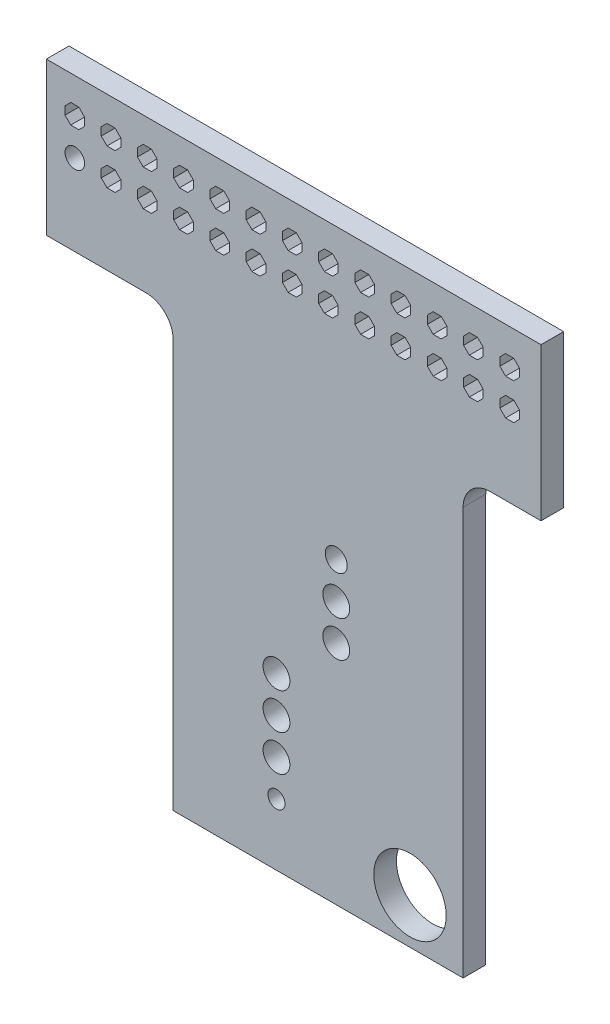
SolidWorks part; units mm, degrees
ref_plane "Front Plane" through (0, 0, 0) normal (0, 0, 1) x (1, 0, 0)
ref_plane "Top Plane" through (0, 0, 0) normal (0, 1, 0) x (1, 0, 0)
ref_plane "Right Plane" through (0, 0, 0) normal (1, 0, 0) x (0, 0, -1)
sketch "Model" plane through (0, 0, 0) normal (0, 0, 1) x (1, 0, 0)
  line L0 (16.129, 5.2578) -> (16.129, 3.3782) construction
  line L1 (20.32, 21.8948) -> (20.32, 20.0152) construction
  line L8 (19.3802, 21.8948) -> (19.3802, 20.0152) construction
  line L9 (19.3802, 20.0152) -> (21.2598, 20.0152) construction
  line L10 (21.2598, 20.0152) -> (21.2598, 21.8948) construction
  line L11 (21.2598, 21.8948) -> (19.3802, 21.8948) construction
  line L12 (19.3802, 21.8948) -> (19.3802, 20.0152) construction
  line L13 (19.3802, 20.0152) -> (21.2598, 20.0152) construction
  line L14 (21.2598, 20.0152) -> (21.2598, 21.8948) construction
  line L15 (21.2598, 21.8948) -> (19.3802, 21.8948) construction
  line L16 (17.0688, 3.3782) -> (17.0688, 5.2578) construction
  line L17 (17.0688, 5.2578) -> (15.1892, 5.2578) construction
  line L18 (15.1892, 5.2578) -> (15.1892, 3.3782) construction
  line L19 (15.1892, 3.3782) -> (17.0688, 3.3782) construction
  line L20 (17.0688, 3.3782) -> (17.0688, 5.2578) construction
  line L21 (17.0688, 5.2578) -> (15.1892, 5.2578) construction
  line L22 (15.1892, 5.2578) -> (15.1892, 3.3782) construction
  line L23 (15.1892, 3.3782) -> (17.0688, 3.3782) construction
  line L24 (8.89, 0) -> (29.21, 0)
  line L25 (34.671, 41.1734) -> (0, 41.1734)
  line L26 (0, 41.1734) -> (0, 30.48)
  line L27 (0, 30.48) -> (6.985, 30.48)
  line L28 (8.89, 28.575) -> (8.89, 0)
  line L29 (29.21, 28.575) -> (29.21, 0)
  line L30 (34.671, 30.48) -> (34.671, 41.1734)
  line L31 (34.671, 30.48) -> (31.115, 30.48)
  circle A0 centre (16.129, 4.318) radius 0.5995
  circle A1 centre (20.32, 20.955) radius 0.7709
  arc A2 (8.89, 28.575) -> (6.985, 30.48) centre (6.985, 28.575) ccw
  arc A3 (31.115, 30.48) -> (29.21, 28.575) centre (31.115, 28.575) ccw
  circle B0 centre (1.9939, 36.1696) radius 0.6858
  circle B1 centre (1.9939, 36.1696) radius 0.6858
  line B2 (1.3081, 38.4255) -> (1.3081, 38.9937)
  line B3 (1.3081, 38.9937) -> (1.7098, 39.3954)
  line B4 (1.7098, 39.3954) -> (2.278, 39.3954)
  line B5 (2.278, 39.3954) -> (2.6797, 38.9937)
  line B6 (2.6797, 38.9937) -> (2.6797, 38.4255)
  line B7 (2.6797, 38.4255) -> (2.278, 38.0238)
  line B8 (2.278, 38.0238) -> (1.7098, 38.0238)
  line B9 (1.7098, 38.0238) -> (1.3081, 38.4255)
  line B10 (1.3081, 38.4255) -> (1.3081, 38.9937)
  line B11 (1.3081, 38.9937) -> (1.7098, 39.3954)
  line B12 (1.7098, 39.3954) -> (2.278, 39.3954)
  line B13 (2.278, 39.3954) -> (2.6797, 38.9937)
  line B14 (2.6797, 38.9937) -> (2.6797, 38.4255)
  line B15 (2.6797, 38.4255) -> (2.278, 38.0238)
  line B16 (2.278, 38.0238) -> (1.7098, 38.0238)
  line B17 (1.7098, 38.0238) -> (1.3081, 38.4255)
  line B18 (3.8481, 35.8855) -> (3.8481, 36.4537)
  line B19 (3.8481, 36.4537) -> (4.2498, 36.8554)
  line B20 (4.2498, 36.8554) -> (4.818, 36.8554)
  line B21 (4.818, 36.8554) -> (5.2197, 36.4537)
  line B22 (5.2197, 36.4537) -> (5.2197, 35.8855)
  line B23 (5.2197, 35.8855) -> (4.818, 35.4838)
  line B24 (4.818, 35.4838) -> (4.2498, 35.4838)
  line B25 (4.2498, 35.4838) -> (3.8481, 35.8855)
  line B26 (3.8481, 35.8855) -> (3.8481, 36.4537)
  line B27 (3.8481, 36.4537) -> (4.2498, 36.8554)
  line B28 (4.2498, 36.8554) -> (4.818, 36.8554)
  line B29 (4.818, 36.8554) -> (5.2197, 36.4537)
  line B30 (5.2197, 36.4537) -> (5.2197, 35.8855)
  line B31 (5.2197, 35.8855) -> (4.818, 35.4838)
  line B32 (4.818, 35.4838) -> (4.2498, 35.4838)
  line B33 (4.2498, 35.4838) -> (3.8481, 35.8855)
  line B34 (3.8481, 38.4255) -> (3.8481, 38.9937)
  line B35 (3.8481, 38.9937) -> (4.2498, 39.3954)
  line B36 (4.2498, 39.3954) -> (4.818, 39.3954)
  line B37 (4.818, 39.3954) -> (5.2197, 38.9937)
  line B38 (5.2197, 38.9937) -> (5.2197, 38.4255)
  line B39 (5.2197, 38.4255) -> (4.818, 38.0238)
  line B40 (4.818, 38.0238) -> (4.2498, 38.0238)
  line B41 (4.2498, 38.0238) -> (3.8481, 38.4255)
  line B42 (3.8481, 38.4255) -> (3.8481, 38.9937)
  line B43 (3.8481, 38.9937) -> (4.2498, 39.3954)
  line B44 (4.2498, 39.3954) -> (4.818, 39.3954)
  line B45 (4.818, 39.3954) -> (5.2197, 38.9937)
  line B46 (5.2197, 38.9937) -> (5.2197, 38.4255)
  line B47 (5.2197, 38.4255) -> (4.818, 38.0238)
  line B48 (4.818, 38.0238) -> (4.2498, 38.0238)
  line B49 (4.2498, 38.0238) -> (3.8481, 38.4255)
  line B50 (6.3881, 35.8855) -> (6.3881, 36.4537)
  line B51 (6.3881, 36.4537) -> (6.7898, 36.8554)
  line B52 (6.7898, 36.8554) -> (7.358, 36.8554)
  line B53 (7.358, 36.8554) -> (7.7597, 36.4537)
  line B54 (7.7597, 36.4537) -> (7.7597, 35.8855)
  line B55 (7.7597, 35.8855) -> (7.358, 35.4838)
  line B56 (7.358, 35.4838) -> (6.7898, 35.4838)
  line B57 (6.7898, 35.4838) -> (6.3881, 35.8855)
  line B58 (6.3881, 35.8855) -> (6.3881, 36.4537)
  line B59 (6.3881, 36.4537) -> (6.7898, 36.8554)
  line B60 (6.7898, 36.8554) -> (7.358, 36.8554)
  line B61 (7.358, 36.8554) -> (7.7597, 36.4537)
  line B62 (7.7597, 36.4537) -> (7.7597, 35.8855)
  line B63 (7.7597, 35.8855) -> (7.358, 35.4838)
  line B64 (7.358, 35.4838) -> (6.7898, 35.4838)
  line B65 (6.7898, 35.4838) -> (6.3881, 35.8855)
  line B66 (6.3881, 38.4255) -> (6.3881, 38.9937)
  line B67 (6.3881, 38.9937) -> (6.7898, 39.3954)
  line B68 (6.7898, 39.3954) -> (7.358, 39.3954)
  line B69 (7.358, 39.3954) -> (7.7597, 38.9937)
  line B70 (7.7597, 38.9937) -> (7.7597, 38.4255)
  line B71 (7.7597, 38.4255) -> (7.358, 38.0238)
  line B72 (7.358, 38.0238) -> (6.7898, 38.0238)
  line B73 (6.7898, 38.0238) -> (6.3881, 38.4255)
  line B74 (6.3881, 38.4255) -> (6.3881, 38.9937)
  line B75 (6.3881, 38.9937) -> (6.7898, 39.3954)
  line B76 (6.7898, 39.3954) -> (7.358, 39.3954)
  line B77 (7.358, 39.3954) -> (7.7597, 38.9937)
  line B78 (7.7597, 38.9937) -> (7.7597, 38.4255)
  line B79 (7.7597, 38.4255) -> (7.358, 38.0238)
  line B80 (7.358, 38.0238) -> (6.7898, 38.0238)
  line B81 (6.7898, 38.0238) -> (6.3881, 38.4255)
  line B82 (8.9281, 35.8855) -> (8.9281, 36.4537)
  line B83 (8.9281, 36.4537) -> (9.3298, 36.8554)
  line B84 (9.3298, 36.8554) -> (9.898, 36.8554)
  line B85 (9.898, 36.8554) -> (10.2997, 36.4537)
  line B86 (10.2997, 36.4537) -> (10.2997, 35.8855)
  line B87 (10.2997, 35.8855) -> (9.898, 35.4838)
  line B88 (9.898, 35.4838) -> (9.3298, 35.4838)
  line B89 (9.3298, 35.4838) -> (8.9281, 35.8855)
  line B90 (8.9281, 35.8855) -> (8.9281, 36.4537)
  line B91 (8.9281, 36.4537) -> (9.3298, 36.8554)
  line B92 (9.3298, 36.8554) -> (9.898, 36.8554)
  line B93 (9.898, 36.8554) -> (10.2997, 36.4537)
  line B94 (10.2997, 36.4537) -> (10.2997, 35.8855)
  line B95 (10.2997, 35.8855) -> (9.898, 35.4838)
  line B96 (9.898, 35.4838) -> (9.3298, 35.4838)
  line B97 (9.3298, 35.4838) -> (8.9281, 35.8855)
  line B98 (8.9281, 38.4255) -> (8.9281, 38.9937)
  line B99 (8.9281, 38.9937) -> (9.3298, 39.3954)
  line B100 (9.3298, 39.3954) -> (9.898, 39.3954)
  line B101 (9.898, 39.3954) -> (10.2997, 38.9937)
  line B102 (10.2997, 38.9937) -> (10.2997, 38.4255)
  line B103 (10.2997, 38.4255) -> (9.898, 38.0238)
  line B104 (9.898, 38.0238) -> (9.3298, 38.0238)
  line B105 (9.3298, 38.0238) -> (8.9281, 38.4255)
  line B106 (8.9281, 38.4255) -> (8.9281, 38.9937)
  line B107 (8.9281, 38.9937) -> (9.3298, 39.3954)
  line B108 (9.3298, 39.3954) -> (9.898, 39.3954)
  line B109 (9.898, 39.3954) -> (10.2997, 38.9937)
  line B110 (10.2997, 38.9937) -> (10.2997, 38.4255)
  line B111 (10.2997, 38.4255) -> (9.898, 38.0238)
  line B112 (9.898, 38.0238) -> (9.3298, 38.0238)
  line B113 (9.3298, 38.0238) -> (8.9281, 38.4255)
  line B114 (11.4681, 35.8855) -> (11.4681, 36.4537)
  line B115 (11.4681, 36.4537) -> (11.8698, 36.8554)
  line B116 (11.8698, 36.8554) -> (12.438, 36.8554)
  line B117 (12.438, 36.8554) -> (12.8397, 36.4537)
  line B118 (12.8397, 36.4537) -> (12.8397, 35.8855)
  line B119 (12.8397, 35.8855) -> (12.438, 35.4838)
  line B120 (12.438, 35.4838) -> (11.8698, 35.4838)
  line B121 (11.8698, 35.4838) -> (11.4681, 35.8855)
  line B122 (11.4681, 35.8855) -> (11.4681, 36.4537)
  line B123 (11.4681, 36.4537) -> (11.8698, 36.8554)
  line B124 (11.8698, 36.8554) -> (12.438, 36.8554)
  line B125 (12.438, 36.8554) -> (12.8397, 36.4537)
  line B126 (12.8397, 36.4537) -> (12.8397, 35.8855)
  line B127 (12.8397, 35.8855) -> (12.438, 35.4838)
  line B128 (12.438, 35.4838) -> (11.8698, 35.4838)
  line B129 (11.8698, 35.4838) -> (11.4681, 35.8855)
  line B130 (11.4681, 38.4255) -> (11.4681, 38.9937)
  line B131 (11.4681, 38.9937) -> (11.8698, 39.3954)
  line B132 (11.8698, 39.3954) -> (12.438, 39.3954)
  line B133 (12.438, 39.3954) -> (12.8397, 38.9937)
  line B134 (12.8397, 38.9937) -> (12.8397, 38.4255)
  line B135 (12.8397, 38.4255) -> (12.438, 38.0238)
  line B136 (12.438, 38.0238) -> (11.8698, 38.0238)
  line B137 (11.8698, 38.0238) -> (11.4681, 38.4255)
  line B138 (11.4681, 38.4255) -> (11.4681, 38.9937)
  line B139 (11.4681, 38.9937) -> (11.8698, 39.3954)
  line B140 (11.8698, 39.3954) -> (12.438, 39.3954)
  line B141 (12.438, 39.3954) -> (12.8397, 38.9937)
  line B142 (12.8397, 38.9937) -> (12.8397, 38.4255)
  line B143 (12.8397, 38.4255) -> (12.438, 38.0238)
  line B144 (12.438, 38.0238) -> (11.8698, 38.0238)
  line B145 (11.8698, 38.0238) -> (11.4681, 38.4255)
  line B146 (14.0081, 35.8855) -> (14.0081, 36.4537)
  line B147 (14.0081, 36.4537) -> (14.4098, 36.8554)
  line B148 (14.4098, 36.8554) -> (14.978, 36.8554)
  line B149 (14.978, 36.8554) -> (15.3797, 36.4537)
  line B150 (15.3797, 36.4537) -> (15.3797, 35.8855)
  line B151 (15.3797, 35.8855) -> (14.978, 35.4838)
  line B152 (14.978, 35.4838) -> (14.4098, 35.4838)
  line B153 (14.4098, 35.4838) -> (14.0081, 35.8855)
  line B154 (14.0081, 35.8855) -> (14.0081, 36.4537)
  line B155 (14.0081, 36.4537) -> (14.4098, 36.8554)
  line B156 (14.4098, 36.8554) -> (14.978, 36.8554)
  line B157 (14.978, 36.8554) -> (15.3797, 36.4537)
  line B158 (15.3797, 36.4537) -> (15.3797, 35.8855)
  line B159 (15.3797, 35.8855) -> (14.978, 35.4838)
  line B160 (14.978, 35.4838) -> (14.4098, 35.4838)
  line B161 (14.4098, 35.4838) -> (14.0081, 35.8855)
  line B162 (14.0081, 38.4255) -> (14.0081, 38.9937)
  line B163 (14.0081, 38.9937) -> (14.4098, 39.3954)
  line B164 (14.4098, 39.3954) -> (14.978, 39.3954)
  line B165 (14.978, 39.3954) -> (15.3797, 38.9937)
  line B166 (15.3797, 38.9937) -> (15.3797, 38.4255)
  line B167 (15.3797, 38.4255) -> (14.978, 38.0238)
  line B168 (14.978, 38.0238) -> (14.4098, 38.0238)
  line B169 (14.4098, 38.0238) -> (14.0081, 38.4255)
  line B170 (14.0081, 38.4255) -> (14.0081, 38.9937)
  line B171 (14.0081, 38.9937) -> (14.4098, 39.3954)
  line B172 (14.4098, 39.3954) -> (14.978, 39.3954)
  line B173 (14.978, 39.3954) -> (15.3797, 38.9937)
  line B174 (15.3797, 38.9937) -> (15.3797, 38.4255)
  line B175 (15.3797, 38.4255) -> (14.978, 38.0238)
  line B176 (14.978, 38.0238) -> (14.4098, 38.0238)
  line B177 (14.4098, 38.0238) -> (14.0081, 38.4255)
  line B178 (16.5481, 35.8855) -> (16.5481, 36.4537)
  line B179 (16.5481, 36.4537) -> (16.9498, 36.8554)
  line B180 (16.9498, 36.8554) -> (17.518, 36.8554)
  line B181 (17.518, 36.8554) -> (17.9197, 36.4537)
  line B182 (17.9197, 36.4537) -> (17.9197, 35.8855)
  line B183 (17.9197, 35.8855) -> (17.518, 35.4838)
  line B184 (17.518, 35.4838) -> (16.9498, 35.4838)
  line B185 (16.9498, 35.4838) -> (16.5481, 35.8855)
  line B186 (16.5481, 35.8855) -> (16.5481, 36.4537)
  line B187 (16.5481, 36.4537) -> (16.9498, 36.8554)
  line B188 (16.9498, 36.8554) -> (17.518, 36.8554)
  line B189 (17.518, 36.8554) -> (17.9197, 36.4537)
  line B190 (17.9197, 36.4537) -> (17.9197, 35.8855)
  line B191 (17.9197, 35.8855) -> (17.518, 35.4838)
  line B192 (17.518, 35.4838) -> (16.9498, 35.4838)
  line B193 (16.9498, 35.4838) -> (16.5481, 35.8855)
  line B194 (16.5481, 38.4255) -> (16.5481, 38.9937)
  line B195 (16.5481, 38.9937) -> (16.9498, 39.3954)
  line B196 (16.9498, 39.3954) -> (17.518, 39.3954)
  line B197 (17.518, 39.3954) -> (17.9197, 38.9937)
  line B198 (17.9197, 38.9937) -> (17.9197, 38.4255)
  line B199 (17.9197, 38.4255) -> (17.518, 38.0238)
  line B200 (17.518, 38.0238) -> (16.9498, 38.0238)
  line B201 (16.9498, 38.0238) -> (16.5481, 38.4255)
  line B202 (16.5481, 38.4255) -> (16.5481, 38.9937)
  line B203 (16.5481, 38.9937) -> (16.9498, 39.3954)
  line B204 (16.9498, 39.3954) -> (17.518, 39.3954)
  line B205 (17.518, 39.3954) -> (17.9197, 38.9937)
  line B206 (17.9197, 38.9937) -> (17.9197, 38.4255)
  line B207 (17.9197, 38.4255) -> (17.518, 38.0238)
  line B208 (17.518, 38.0238) -> (16.9498, 38.0238)
  line B209 (16.9498, 38.0238) -> (16.5481, 38.4255)
  line B210 (19.0881, 35.8855) -> (19.0881, 36.4537)
  line B211 (19.0881, 36.4537) -> (19.4898, 36.8554)
  line B212 (19.4898, 36.8554) -> (20.058, 36.8554)
  line B213 (20.058, 36.8554) -> (20.4597, 36.4537)
  line B214 (20.4597, 36.4537) -> (20.4597, 35.8855)
  line B215 (20.4597, 35.8855) -> (20.058, 35.4838)
  line B216 (20.058, 35.4838) -> (19.4898, 35.4838)
  line B217 (19.4898, 35.4838) -> (19.0881, 35.8855)
  line B218 (19.0881, 35.8855) -> (19.0881, 36.4537)
  line B219 (19.0881, 36.4537) -> (19.4898, 36.8554)
  line B220 (19.4898, 36.8554) -> (20.058, 36.8554)
  line B221 (20.058, 36.8554) -> (20.4597, 36.4537)
  line B222 (20.4597, 36.4537) -> (20.4597, 35.8855)
  line B223 (20.4597, 35.8855) -> (20.058, 35.4838)
  line B224 (20.058, 35.4838) -> (19.4898, 35.4838)
  line B225 (19.4898, 35.4838) -> (19.0881, 35.8855)
  line B226 (19.0881, 38.4255) -> (19.0881, 38.9937)
  line B227 (19.0881, 38.9937) -> (19.4898, 39.3954)
  line B228 (19.4898, 39.3954) -> (20.058, 39.3954)
  line B229 (20.058, 39.3954) -> (20.4597, 38.9937)
  line B230 (20.4597, 38.9937) -> (20.4597, 38.4255)
  line B231 (20.4597, 38.4255) -> (20.058, 38.0238)
  line B232 (20.058, 38.0238) -> (19.4898, 38.0238)
  line B233 (19.4898, 38.0238) -> (19.0881, 38.4255)
  line B234 (19.0881, 38.4255) -> (19.0881, 38.9937)
  line B235 (19.0881, 38.9937) -> (19.4898, 39.3954)
  line B236 (19.4898, 39.3954) -> (20.058, 39.3954)
  line B237 (20.058, 39.3954) -> (20.4597, 38.9937)
  line B238 (20.4597, 38.9937) -> (20.4597, 38.4255)
  line B239 (20.4597, 38.4255) -> (20.058, 38.0238)
  line B240 (20.058, 38.0238) -> (19.4898, 38.0238)
  line B241 (19.4898, 38.0238) -> (19.0881, 38.4255)
  line B242 (21.6281, 35.8855) -> (21.6281, 36.4537)
  line B243 (21.6281, 36.4537) -> (22.0298, 36.8554)
  line B244 (22.0298, 36.8554) -> (22.598, 36.8554)
  line B245 (22.598, 36.8554) -> (22.9997, 36.4537)
  line B246 (22.9997, 36.4537) -> (22.9997, 35.8855)
  line B247 (22.9997, 35.8855) -> (22.598, 35.4838)
  line B248 (22.598, 35.4838) -> (22.0298, 35.4838)
  line B249 (22.0298, 35.4838) -> (21.6281, 35.8855)
  line B250 (21.6281, 35.8855) -> (21.6281, 36.4537)
  line B251 (21.6281, 36.4537) -> (22.0298, 36.8554)
  line B252 (22.0298, 36.8554) -> (22.598, 36.8554)
  line B253 (22.598, 36.8554) -> (22.9997, 36.4537)
  line B254 (22.9997, 36.4537) -> (22.9997, 35.8855)
  line B255 (22.9997, 35.8855) -> (22.598, 35.4838)
  line B256 (22.598, 35.4838) -> (22.0298, 35.4838)
  line B257 (22.0298, 35.4838) -> (21.6281, 35.8855)
  line B258 (21.6281, 38.4255) -> (21.6281, 38.9937)
  line B259 (21.6281, 38.9937) -> (22.0298, 39.3954)
  line B260 (22.0298, 39.3954) -> (22.598, 39.3954)
  line B261 (22.598, 39.3954) -> (22.9997, 38.9937)
  line B262 (22.9997, 38.9937) -> (22.9997, 38.4255)
  line B263 (22.9997, 38.4255) -> (22.598, 38.0238)
  line B264 (22.598, 38.0238) -> (22.0298, 38.0238)
  line B265 (22.0298, 38.0238) -> (21.6281, 38.4255)
  line B266 (21.6281, 38.4255) -> (21.6281, 38.9937)
  line B267 (21.6281, 38.9937) -> (22.0298, 39.3954)
  line B268 (22.0298, 39.3954) -> (22.598, 39.3954)
  line B269 (22.598, 39.3954) -> (22.9997, 38.9937)
  line B270 (22.9997, 38.9937) -> (22.9997, 38.4255)
  line B271 (22.9997, 38.4255) -> (22.598, 38.0238)
  line B272 (22.598, 38.0238) -> (22.0298, 38.0238)
  line B273 (22.0298, 38.0238) -> (21.6281, 38.4255)
  line B274 (24.1681, 35.8855) -> (24.1681, 36.4537)
  line B275 (24.1681, 36.4537) -> (24.5698, 36.8554)
  line B276 (24.5698, 36.8554) -> (25.138, 36.8554)
  line B277 (25.138, 36.8554) -> (25.5397, 36.4537)
  line B278 (25.5397, 36.4537) -> (25.5397, 35.8855)
  line B279 (25.5397, 35.8855) -> (25.138, 35.4838)
  line B280 (25.138, 35.4838) -> (24.5698, 35.4838)
  line B281 (24.5698, 35.4838) -> (24.1681, 35.8855)
  line B282 (24.1681, 35.8855) -> (24.1681, 36.4537)
  line B283 (24.1681, 36.4537) -> (24.5698, 36.8554)
  line B284 (24.5698, 36.8554) -> (25.138, 36.8554)
  line B285 (25.138, 36.8554) -> (25.5397, 36.4537)
  line B286 (25.5397, 36.4537) -> (25.5397, 35.8855)
  line B287 (25.5397, 35.8855) -> (25.138, 35.4838)
  line B288 (25.138, 35.4838) -> (24.5698, 35.4838)
  line B289 (24.5698, 35.4838) -> (24.1681, 35.8855)
  line B290 (24.1681, 38.4255) -> (24.1681, 38.9937)
  line B291 (24.1681, 38.9937) -> (24.5698, 39.3954)
  line B292 (24.5698, 39.3954) -> (25.138, 39.3954)
  line B293 (25.138, 39.3954) -> (25.5397, 38.9937)
  line B294 (25.5397, 38.9937) -> (25.5397, 38.4255)
  line B295 (25.5397, 38.4255) -> (25.138, 38.0238)
  line B296 (25.138, 38.0238) -> (24.5698, 38.0238)
  line B297 (24.5698, 38.0238) -> (24.1681, 38.4255)
  line B298 (24.1681, 38.4255) -> (24.1681, 38.9937)
  line B299 (24.1681, 38.9937) -> (24.5698, 39.3954)
  line B300 (24.5698, 39.3954) -> (25.138, 39.3954)
  line B301 (25.138, 39.3954) -> (25.5397, 38.9937)
  line B302 (25.5397, 38.9937) -> (25.5397, 38.4255)
  line B303 (25.5397, 38.4255) -> (25.138, 38.0238)
  line B304 (25.138, 38.0238) -> (24.5698, 38.0238)
  line B305 (24.5698, 38.0238) -> (24.1681, 38.4255)
  line B306 (26.7081, 35.8855) -> (26.7081, 36.4537)
  line B307 (26.7081, 36.4537) -> (27.1098, 36.8554)
  line B308 (27.1098, 36.8554) -> (27.678, 36.8554)
  line B309 (27.678, 36.8554) -> (28.0797, 36.4537)
  line B310 (28.0797, 36.4537) -> (28.0797, 35.8855)
  line B311 (28.0797, 35.8855) -> (27.678, 35.4838)
  line B312 (27.678, 35.4838) -> (27.1098, 35.4838)
  line B313 (27.1098, 35.4838) -> (26.7081, 35.8855)
  line B314 (26.7081, 35.8855) -> (26.7081, 36.4537)
  line B315 (26.7081, 36.4537) -> (27.1098, 36.8554)
  line B316 (27.1098, 36.8554) -> (27.678, 36.8554)
  line B317 (27.678, 36.8554) -> (28.0797, 36.4537)
  line B318 (28.0797, 36.4537) -> (28.0797, 35.8855)
  line B319 (28.0797, 35.8855) -> (27.678, 35.4838)
  line B320 (27.678, 35.4838) -> (27.1098, 35.4838)
  line B321 (27.1098, 35.4838) -> (26.7081, 35.8855)
  line B322 (26.7081, 38.4255) -> (26.7081, 38.9937)
  line B323 (26.7081, 38.9937) -> (27.1098, 39.3954)
  line B324 (27.1098, 39.3954) -> (27.678, 39.3954)
  line B325 (27.678, 39.3954) -> (28.0797, 38.9937)
  line B326 (28.0797, 38.9937) -> (28.0797, 38.4255)
  line B327 (28.0797, 38.4255) -> (27.678, 38.0238)
  line B328 (27.678, 38.0238) -> (27.1098, 38.0238)
  line B329 (27.1098, 38.0238) -> (26.7081, 38.4255)
  line B330 (26.7081, 38.4255) -> (26.7081, 38.9937)
  line B331 (26.7081, 38.9937) -> (27.1098, 39.3954)
  line B332 (27.1098, 39.3954) -> (27.678, 39.3954)
  line B333 (27.678, 39.3954) -> (28.0797, 38.9937)
  line B334 (28.0797, 38.9937) -> (28.0797, 38.4255)
  line B335 (28.0797, 38.4255) -> (27.678, 38.0238)
  line B336 (27.678, 38.0238) -> (27.1098, 38.0238)
  line B337 (27.1098, 38.0238) -> (26.7081, 38.4255)
  line B338 (29.2481, 35.8855) -> (29.2481, 36.4537)
  line B339 (29.2481, 36.4537) -> (29.6498, 36.8554)
  line B340 (29.6498, 36.8554) -> (30.218, 36.8554)
  line B341 (30.218, 36.8554) -> (30.6197, 36.4537)
  line B342 (30.6197, 36.4537) -> (30.6197, 35.8855)
  line B343 (30.6197, 35.8855) -> (30.218, 35.4838)
  line B344 (30.218, 35.4838) -> (29.6498, 35.4838)
  line B345 (29.6498, 35.4838) -> (29.2481, 35.8855)
  line B346 (29.2481, 35.8855) -> (29.2481, 36.4537)
  line B347 (29.2481, 36.4537) -> (29.6498, 36.8554)
  line B348 (29.6498, 36.8554) -> (30.218, 36.8554)
  line B349 (30.218, 36.8554) -> (30.6197, 36.4537)
  line B350 (30.6197, 36.4537) -> (30.6197, 35.8855)
  line B351 (30.6197, 35.8855) -> (30.218, 35.4838)
  line B352 (30.218, 35.4838) -> (29.6498, 35.4838)
  line B353 (29.6498, 35.4838) -> (29.2481, 35.8855)
  line B354 (29.2481, 38.4255) -> (29.2481, 38.9937)
  line B355 (29.2481, 38.9937) -> (29.6498, 39.3954)
  line B356 (29.6498, 39.3954) -> (30.218, 39.3954)
  line B357 (30.218, 39.3954) -> (30.6197, 38.9937)
  line B358 (30.6197, 38.9937) -> (30.6197, 38.4255)
  line B359 (30.6197, 38.4255) -> (30.218, 38.0238)
  line B360 (30.218, 38.0238) -> (29.6498, 38.0238)
  line B361 (29.6498, 38.0238) -> (29.2481, 38.4255)
  line B362 (29.2481, 38.4255) -> (29.2481, 38.9937)
  line B363 (29.2481, 38.9937) -> (29.6498, 39.3954)
  line B364 (29.6498, 39.3954) -> (30.218, 39.3954)
  line B365 (30.218, 39.3954) -> (30.6197, 38.9937)
  line B366 (30.6197, 38.9937) -> (30.6197, 38.4255)
  line B367 (30.6197, 38.4255) -> (30.218, 38.0238)
  line B368 (30.218, 38.0238) -> (29.6498, 38.0238)
  line B369 (29.6498, 38.0238) -> (29.2481, 38.4255)
  line B370 (31.7881, 35.8855) -> (31.7881, 36.4537)
  line B371 (31.7881, 36.4537) -> (32.1898, 36.8554)
  line B372 (32.1898, 36.8554) -> (32.758, 36.8554)
  line B373 (32.758, 36.8554) -> (33.1597, 36.4537)
  line B374 (33.1597, 36.4537) -> (33.1597, 35.8855)
  line B375 (33.1597, 35.8855) -> (32.758, 35.4838)
  line B376 (32.758, 35.4838) -> (32.1898, 35.4838)
  line B377 (32.1898, 35.4838) -> (31.7881, 35.8855)
  line B378 (31.7881, 35.8855) -> (31.7881, 36.4537)
  line B379 (31.7881, 36.4537) -> (32.1898, 36.8554)
  line B380 (32.1898, 36.8554) -> (32.758, 36.8554)
  line B381 (32.758, 36.8554) -> (33.1597, 36.4537)
  line B382 (33.1597, 36.4537) -> (33.1597, 35.8855)
  line B383 (33.1597, 35.8855) -> (32.758, 35.4838)
  line B384 (32.758, 35.4838) -> (32.1898, 35.4838)
  line B385 (32.1898, 35.4838) -> (31.7881, 35.8855)
  line B386 (31.7881, 38.4255) -> (31.7881, 38.9937)
  line B387 (31.7881, 38.9937) -> (32.1898, 39.3954)
  line B388 (32.1898, 39.3954) -> (32.758, 39.3954)
  line B389 (32.758, 39.3954) -> (33.1597, 38.9937)
  line B390 (33.1597, 38.9937) -> (33.1597, 38.4255)
  line B391 (33.1597, 38.4255) -> (32.758, 38.0238)
  line B392 (32.758, 38.0238) -> (32.1898, 38.0238)
  line B393 (32.1898, 38.0238) -> (31.7881, 38.4255)
  line B394 (31.7881, 38.4255) -> (31.7881, 38.9937)
  line B395 (31.7881, 38.9937) -> (32.1898, 39.3954)
  line B396 (32.1898, 39.3954) -> (32.758, 39.3954)
  line B397 (32.758, 39.3954) -> (33.1597, 38.9937)
  line B398 (33.1597, 38.9937) -> (33.1597, 38.4255)
  line B399 (33.1597, 38.4255) -> (32.758, 38.0238)
  line B400 (32.758, 38.0238) -> (32.1898, 38.0238)
  line B401 (32.1898, 38.0238) -> (31.7881, 38.4255)
  circle B402 centre (20.32, 18.415) radius 0.9398
  circle B403 centre (20.32, 18.415) radius 0.9398
  circle B404 centre (20.32, 15.875) radius 0.9398
  circle B405 centre (20.32, 15.875) radius 0.9398
  circle B406 centre (16.129, 6.858) radius 0.9398
  circle B407 centre (16.129, 6.858) radius 0.9398
  circle B408 centre (16.129, 9.398) radius 0.9398
  circle B409 centre (16.129, 9.398) radius 0.9398
  circle B410 centre (16.129, 11.938) radius 0.9398
  circle B411 centre (16.129, 11.938) radius 0.9398
  circle B412 centre (25.4889, 3.175) radius 2.54
  circle B413 centre (25.4889, 3.175) radius 2.54
sketch_block_instance "ROUNDP-1"
sketch_block "ROUNDP"
sketch_block_instance "ROUNDP-2"
sketch_block_instance "OCTAGONP-1"
sketch_block "OCTAGONP"
sketch_block_instance "OCTAGONP-2"
sketch_block_instance "OCTAGONP-3"
sketch_block_instance "OCTAGONP-4"
sketch_block_instance "OCTAGONP-5"
sketch_block_instance "OCTAGONP-6"
sketch_block_instance "OCTAGONP-7"
sketch_block_instance "OCTAGONP-8"
sketch_block_instance "OCTAGONP-9"
sketch_block_instance "OCTAGONP-10"
sketch_block_instance "OCTAGONP-11"
sketch_block_instance "OCTAGONP-12"
sketch_block_instance "OCTAGONP-13"
sketch_block_instance "OCTAGONP-14"
sketch_block_instance "OCTAGONP-15"
sketch_block_instance "OCTAGONP-16"
sketch_block_instance "OCTAGONP-17"
sketch_block_instance "OCTAGONP-18"
sketch_block_instance "OCTAGONP-19"
sketch_block_instance "OCTAGONP-20"
sketch_block_instance "OCTAGONP-21"
sketch_block_instance "OCTAGONP-22"
sketch_block_instance "OCTAGONP-23"
sketch_block_instance "OCTAGONP-24"
sketch_block_instance "OCTAGONP-25"
sketch_block_instance "OCTAGONP-26"
sketch_block_instance "OCTAGONP-27"
sketch_block_instance "OCTAGONP-28"
sketch_block_instance "OCTAGONP-29"
sketch_block_instance "OCTAGONP-30"
sketch_block_instance "OCTAGONP-31"
sketch_block_instance "OCTAGONP-32"
sketch_block_instance "OCTAGONP-33"
sketch_block_instance "OCTAGONP-34"
sketch_block_instance "OCTAGONP-35"
sketch_block_instance "OCTAGONP-36"
sketch_block_instance "OCTAGONP-37"
sketch_block_instance "OCTAGONP-38"
sketch_block_instance "OCTAGONP-39"
sketch_block_instance "OCTAGONP-40"
sketch_block_instance "OCTAGONP-41"
sketch_block_instance "OCTAGONP-42"
sketch_block_instance "OCTAGONP-43"
sketch_block_instance "OCTAGONP-44"
sketch_block_instance "OCTAGONP-45"
sketch_block_instance "OCTAGONP-46"
sketch_block_instance "OCTAGONP-47"
sketch_block_instance "OCTAGONP-48"
sketch_block_instance "OCTAGONP-49"
sketch_block_instance "OCTAGONP-50"
sketch_block_instance "ROUNDP-3"
sketch_block_instance "ROUNDP-4"
sketch_block_instance "ROUNDP-5"
sketch_block_instance "ROUNDP-6"
sketch_block_instance "ROUNDP-7"
sketch_block_instance "ROUNDP-8"
sketch_block_instance "ROUNDP-9"
sketch_block_instance "ROUNDP-10"
sketch_block_instance "ROUNDP-11"
sketch_block_instance "ROUNDP-12"
sketch_block_instance "ROUNDV-1"
sketch_block "ROUNDV"
sketch_block_instance "ROUNDV-2"
extrude "Boss-Extrude1" add sketch "Model" along normal blind 1.5875 contours A3 L31 L30 L25 L26 L27 A2 L28 L24 L29 B412 B410 B408 B406 B404 B402 B376 B377 B370 B371 B372 B373 B374 B375 B344 B345 B338 B339 B340 B341 B342 B343 B312 B313 B306 B307 B308 B309 B310 B311 B280
